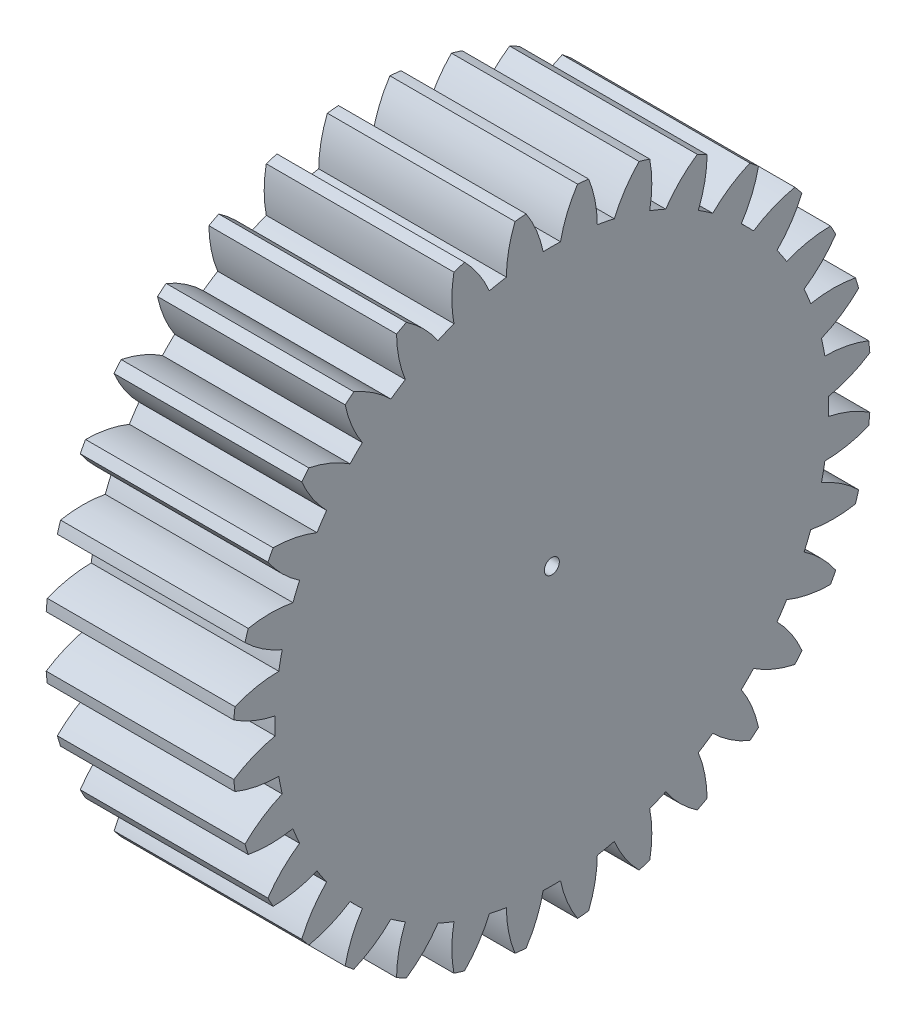
SolidWorks part; units mm, degrees
ref_plane "Plane1" through (0, 0, 0) normal (0, 0, 1) x (1, 0, 0)
ref_plane "Plane2" through (0, 0, 0) normal (0, 1, 0) x (1, 0, 0)
ref_plane "Plane3" through (0, 0, 0) normal (1, 0, 0) x (0, 0, -1)
sketch "HoldingSke" plane through (0, 0, 0) normal (0, 1, 0) x (1, 0, 0)
  line L0 (0, 0) -> (0.848, -0.5299)
  line L1 (-15, 0) -> (100, 0) construction
  line L2 (0, 0) -> (-2.1039, 2.3779)
  line L3 (0, 0) -> (-11.863, 4.5341)
  line L4 (0, 0) -> (7.3237, 4.5764)
  line L5 (0, 0) -> (-46.8476, -17.4728)
  line L6 (0, 0) -> (-8.2896, -5.593)
  line L7 (-2.1039, 2.3779) -> (8.6586, 51.2059)
  line L8 (-76.2, 54.61) -> (-76.1, 54.61)
  line L9 (-71.009, 38.7566) -> (-53.1078, 45.2721)
  line L10 (-76.2, 71.12) -> (104.1128, 71.12)
  line L11 (0, 0) -> (-10, 0)
  line L12 (-76.2, 101.6) -> (-76.162, 101.6)
  line L13 (24.9733, 27.94) -> (52.9518, 28.4284)
  line L14 (24.9733, 27.94) -> (24.9743, 27.94)
  line L15 (24.9733, 27.94) -> (100.4006, 29.5858)
  line L16 (-63.627, -1) -> (-12.827, -1)
  circle A0 centre (0, 0) radius 0.4
  circle A1 centre (0, 0) radius 14.749
  circle A2 centre (0, 0) radius 37.5
  circle A3 centre (0, 0) radius 0.4
  dimension "MHD" = 29.498
  dimension "Hub_dia" = 75
  dimension "Bore" = 0.8
  dimension "MBD" = 0.8
  dimension "Num_teeth" = 32
  dimension "Pitch" = 1
  dimension "Overall_len" = 50
  dimension "Show_teeth" = 32
  dimension "Thickness" = 10
  dimension "OAL" = 50.0001
  dimension "T_dim" = 0.1
  dimension "Ap" = 20
  dimension "H" = 19.05
  dimension "Pitch_radius" = 180.3128
  dimension "Width" = 10
  dimension "Backlash" = 0.038
  dimension "Addendum_fac" = 1
  dimension "Dedendum_fac" = 1.25
  dimension "Clearance_fac" = 0.25
  dimension "Dedendum_add" = 0.001
  dimension "Module" = 1
sketch "BasProSke" plane through (0, 0, 0) normal (0, 1, 0) x (1, 0, 0)
  line L0 (-10, 0) -> (60, 0) construction
  line L1 (0, 0) -> (0, 17)
  line L2 (0, 0) -> (10, 0)
  line L3 (10, 0) -> (10, 17)
  line L4 (10, 17) -> (0, 17)
  dimension "Thickness" = 10
  dimension "Diameter" = 34
revolve "Base-Revolve" add sketch "BasProSke" angle 360 about L0
sketch "TooCutSke" plane through (0, 0, 0) normal (1, 0, 0) x (0, 0, -1)
  line L1 (0, 0) -> (0, 107) construction
  line L2 (0, 0) -> (-0.8516, 15.9773) construction
  line L3 (0, 0) -> (-3.1334, 31.8138) construction
  line L4 (-0.8516, 15.9773) -> (-1.5667, 15.9069) construction
  arc A0 (0.462, 14.7418) -> (-0.462, 14.7418) centre (0, 0) ccw
  arc A1 (1.3867, 16.9688) -> (-1.3867, 16.9688) centre (0, 0) ccw
  circle A2 centre (0, 0) radius 16 construction
  circle A3 centre (0, 0) radius 15.0351 construction
  arc A4 (-0.462, 14.7418) -> (-1.3867, 16.9688) centre (-6.7293, 13.4451) ccw
  arc A5 (1.3867, 16.9688) -> (0.462, 14.7418) centre (6.7293, 13.4451) ccw
  dimension "Root_dia" = 29.498
  dimension "Overcut_dia" = 34.0508
  dimension "Pitch_dia" = 32
  dimension "Base_dia" = 30.0702
  dimension "Flank_rad" = 6.4
  dimension "Half_ang" = 5.625
  dimension "Half_CT" = 0.7186
extrude "ToothCut" cut sketch "TooCutSke" along normal through all
fillet "Breaks" [suppressed] radius 0.02
fillet "RootFillets" [suppressed] radius 0.251
pattern_circular "TeethCuts" count 32 every 11.25 about axis through (-10, 0, 0) along (1, 0, 0) of "ToothCut", "RootFillets", "Breaks"
sketch "HubNeaOneSke" plane through (0, 0, 0) normal (-1, 0, 0) x (0, 0, 1)
  circle A0 centre (0, 0) radius 14.749
  dimension "Diameter" = 29.498
extrude "HubNearOne" [suppressed] add sketch "HubNeaOneSke" along normal blind 40.0001
sketch "HubNeaBotSke" plane through (0, 0, 0) normal (-1, 0, 0) x (0, 0, 1)
  circle A0 centre (0, 0) radius 14.749
  dimension "Diameter" = 29.498
extrude "HubNearBoth" [suppressed] add sketch "HubNeaBotSke" along normal blind 20
ref_plane "FarPln" through (10, 0, 0) normal (1, 0, 0) x (0, 0, -1)
sketch "HubFarSke" plane through (10, 0, 0) normal (1, 0, 0) x (0, 0, -1)
  circle A0 centre (0, 0) radius 14.749
  dimension "Diameter" = 29.498
extrude "HubFar" [suppressed] add sketch "HubFarSke" along normal blind 20
sketch "BorSke" plane through (0, 0, 0) normal (1, 0, 0) x (0, 0, -1)
  circle A0 centre (0, 0) radius 0.4
  dimension "Diameter" = 0.8
extrude "Bore" cut sketch "BorSke" along normal mid plane 100.0001
sketch "KeySke" plane through (0, 0, 0) normal (1, 0, 0) x (0, 0, -1)
  line L0 (-0.05, 0) -> (-0.05, 0.5)
  line L1 (-0.05, 0.5) -> (0.05, 0.5)
  line L2 (0.05, 0.5) -> (0.05, 0)
  line L3 (0, 0) -> (0, 34) construction
  line L4 (-0.05, 0) -> (0.05, 0)
  dimension "Offset" = 0.5
  dimension "Width" = 0.1
extrude "Keyway" [suppressed] cut sketch "KeySke" along normal mid plane 100.0001
pattern_circular "Keyway2" [suppressed] count 2 every 90 about axis through (-10, 0, 0) along (1, 0, 0)
equation "' \"Module@HoldingSke\" = 6.35"
equation "' \"Num_teeth@HoldingSke\" = 12"
equation "' \"Ap@HoldingSke\" =  20"
equation "' \"Ap@HoldingSke\" = 20"
equation "' \"Width@HoldingSke\" = 0.5 * 25.4"
equation "' \"Hub_dia@HoldingSke\"= 1 * 25.4"
equation "' \"Hub_dia@HoldingSke\" = 1 * 25.4"
equation "' \"Overall_len@HoldingSke\" = 1.0 * 25.4"
equation "' \"Bore@HoldingSke\" = 0.75 * 25.4"
equation "' \"T_dim@HoldingSke\" = 0.1 * 25.4"
equation "' \"Width@KeySke\" = 0.25 * 25.4"
equation "' \"Show_teeth@HoldingSke\" = 13"
equation "' \"Backlash@HoldingSke\" = 0.009 * 25.4"
equation "' \"Addendum_fac@HoldingSke\" = 1.0"
equation "' \"Dedendum_fac@HoldingSke\" = 1.25"
equation "' \"Dedendum_add@HoldingSke\" = 0.00005 * 25.4"
equation "' \"Clearance_fac@HoldingSke\" = 0.25"
equation "\"Pitch@HoldingSke\" = 1 / \"Module@HoldingSke\""
equation "\"Overcut_dia@TooCutSke\" = (\"Num_teeth@HoldingSke\" + 2 * \"Addendum_fac@HoldingSke\") / \"Pitch@HoldingSke\" + 0.002 * 25.4"
equation "\"Pitch_dia@TooCutSke\" = \"Num_teeth@HoldingSke\" / \"Pitch@HoldingSke\""
equation "\"Base_dia@TooCutSke\" = \"Num_teeth@HoldingSke\" / \"Pitch@HoldingSke\" * cos((\"Ap@HoldingSke\"  * 3.14159265 / 180))"
equation "\"Root_dia@TooCutSke\" = (\"Num_teeth@HoldingSke\" + 2) / \"Pitch@HoldingSke\" - 2 * (\"Addendum_fac@HoldingSke\" + \"Dedendum_fac@HoldingSke\") / \"Pitch@HoldingSke\" - \"Dedendum_add@HoldingSke\" * 2"
equation "\"Half_ang@TooCutSke\" = 180 / \"Num_teeth@HoldingSke\""
equation "\"Half_CT@TooCutSke\" = \"Num_teeth@HoldingSke\" / \"Pitch@HoldingSke\" * sin((3.14159265 / 2 / \"Num_teeth@HoldingSke\")) / 2 - 7 * \"Backlash@HoldingSke\" / 4"
equation "\"Flank_rad@TooCutSke\" = \"Num_teeth@HoldingSke\" / \"Pitch@HoldingSke\" / 5"
equation "\"Radius@RootFillets\" = \"Clearance_fac@HoldingSke\" / \"Pitch@HoldingSke\" + \"Dedendum_add@HoldingSke\""
equation "\"Break_rad@Breaks\" = 0.02 / \"Pitch@HoldingSke\""
equation "\"Thickness@HoldingSke\" = \"Width@HoldingSke\""
equation "\"OAL@HoldingSke\" = \"Thickness@HoldingSke\""
equation "\"MHD@HoldingSke\" = (\"Num_teeth@HoldingSke\" + 2) / \"Pitch@HoldingSke\" - 2 * (\"Addendum_fac@HoldingSke\" + \"Dedendum_fac@HoldingSke\")  / \"Pitch@HoldingSke\" - \"Dedendum_add@HoldingSke\" * 2"
equation "\"MBD@HoldingSke\" = (\"Num_teeth@HoldingSke\" + 2) / \"Pitch@HoldingSke\" - 2 * (\"Addendum_fac@HoldingSke\" + \"Dedendum_fac@HoldingSke\")  / \"Pitch@HoldingSke\" - \"Dedendum_add@HoldingSke\" * 2 - 0.002 * 25.4"
equation "\"MHD@HoldingSke\" = ((sgn( \"MHD@HoldingSke\" - \"Hub_dia@HoldingSke\" )-1)*( \"MHD@HoldingSke\" - \"Hub_dia@HoldingSke\" ))/-2+ \"Hub_dia@HoldingSke\""
equation "\"MBD@HoldingSke\" = ((sgn( \"MBD@HoldingSke\" - \"Bore@HoldingSke\" )-1)*( \"MBD@HoldingSke\" - \"Bore@HoldingSke\" ))/-2+ \"Bore@HoldingSke\""
equation "\"OAL@HoldingSke\" = ((sgn( \"OAL@HoldingSke\" - \"Overall_len@HoldingSke\" )+1)*( \"OAL@HoldingSke\" - \"Overall_len@HoldingSke\" ))/2 + \"Overall_len@HoldingSke\" + 0.000002 * 25.4"
equation "\"Num_teeth@TeethCuts\" = int( \"Show_teeth@HoldingSke\" ) + 1"
equation "\"Num_teeth@TeethCuts\" = ((sgn( \"Num_teeth@TeethCuts\" - \"Num_teeth@HoldingSke\" )-1)*( \"Num_teeth@TeethCuts\" - \"Num_teeth@HoldingSke\" ))/-2+ \"Num_teeth@HoldingSke\""
equation "\"Num_teeth@TeethCuts\" = ((sgn( \"Num_teeth@TeethCuts\" - 2.0)+1)*( \"Num_teeth@TeethCuts\" - 2.0))/2 +2.0"
equation "\"Angle@TeethCuts\" = 360.0 / \"Num_teeth@HoldingSke\""
equation "\"Diameter@BasProSke\" = (\"Num_teeth@HoldingSke\" + 2 * \"Addendum_fac@HoldingSke\") / \"Pitch@HoldingSke\""
equation "\"Thickness@BasProSke\"  = \"Thickness@HoldingSke\""
equation "' \"Fillet_rad@BasProSke\" =  \"Thickness@HoldingSke\" * 0.05"
equation "' \"Fillet_rad@BasProSke\" = \"Thickness@HoldingSke\" * 0.05"
equation "\"MHD@HoldingSke\" = ((sgn( \"MHD@HoldingSke\" - \"Root_dia@TooCutSke\" )-1)*( \"MHD@HoldingSke\" - \"Root_dia@TooCutSke\" ))/-2+ \"Root_dia@TooCutSke\""
equation "\"Diameter@HubNeaOneSke\" = \"MHD@HoldingSke\""
equation "\"Length@HubNearOne\" = \"OAL@HoldingSke\" - \"Thickness@BasProSke\""
equation "\"Diameter@HubNeaBotSke\" = \"MHD@HoldingSke\""
equation "\"Length@HubNearBoth\" = ( \"OAL@HoldingSke\" - \"Thickness@BasProSke\" ) / 2.0"
equation "\"Thickness@FarPln\" = \"Thickness@BasProSke\""
equation "\"Diameter@HubFarSke\" = \"MHD@HoldingSke\""
equation "\"Length@HubFar\" = ( \"OAL@HoldingSke\" - \"Thickness@BasProSke\" ) / 2.0"
equation "\"Diameter@BorSke\" = \"MBD@HoldingSke\""
equation "\"D1@Bore\" = \"OAL@HoldingSke\" * 2.0"
equation "\"D1@Keyway\" = \"OAL@HoldingSke\" * 2.0"
equation "\"Offset@KeySke\" = \"T_dim@HoldingSke\" + \"MBD@HoldingSke\" / 2.0"
